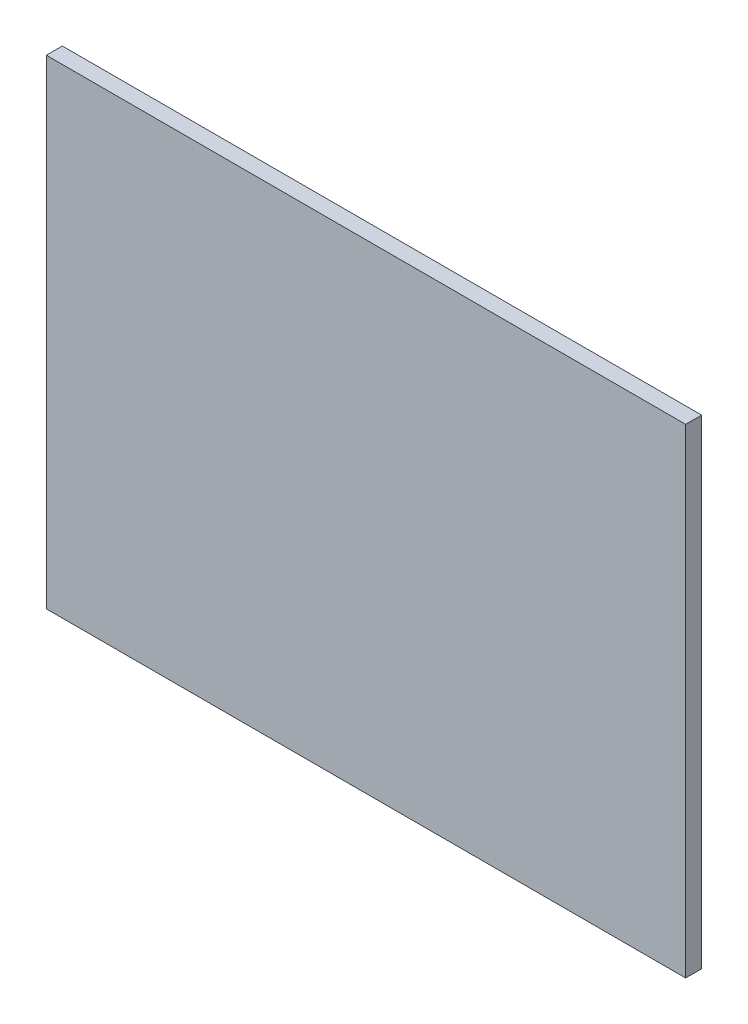
SolidWorks part; units mm, degrees
ref_plane "Front Plane" through (0, 0, 0) normal (0, 0, 1) x (1, 0, 0)
ref_plane "Top Plane" through (0, 0, 0) normal (0, 1, 0) x (1, 0, 0)
ref_plane "Right Plane" through (0, 0, 0) normal (1, 0, 0) x (0, 0, -1)
sketch "Sketch1" plane through (0, 0, 0) normal (0, 0, 1) x (1, 0, 0)
  line L2 (-65.8696, 48.587) -> (14.1304, 48.587)
  line L3 (-65.8696, 48.587) -> (-65.8696, -11.413)
  line L4 (-65.8696, -11.413) -> (14.1304, -11.413)
  line L5 (14.1304, 48.587) -> (14.1304, -11.413)
  dimension "D1" = 80
  dimension "D2" = 60
extrude "Boss-Extrude1" add sketch "Sketch1" along normal blind 2
